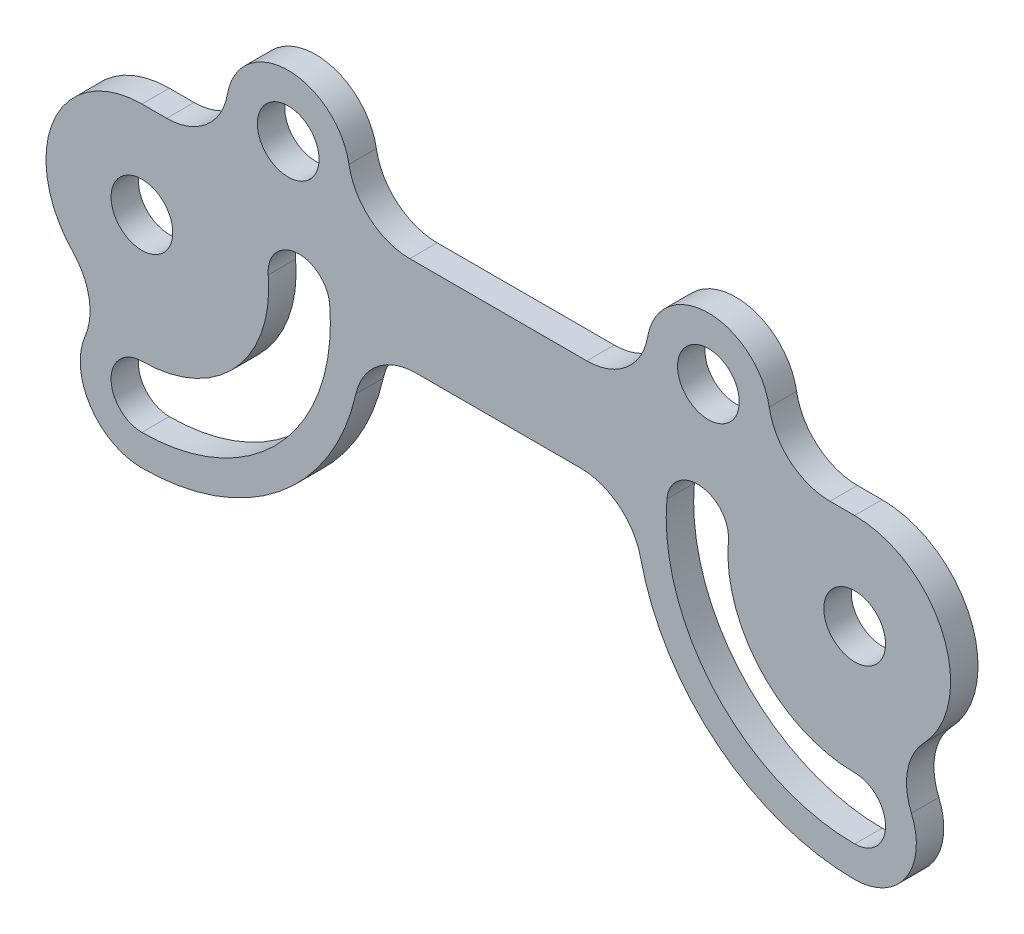
SolidWorks part; units mm, degrees
ref_plane "Front Plane" through (0, 0, 0) normal (0, 0, 1) x (1, 0, 0)
ref_plane "Top Plane" through (0, 0, 0) normal (0, 1, 0) x (1, 0, 0)
ref_plane "Right Plane" through (0, 0, 0) normal (1, 0, 0) x (0, 0, -1)
sketch "Sketch1" plane through (0, 0, 0) normal (0, 0, 1) x (1, 0, 0)
  line L14 (5.5562, 0) -> (35.7188, 0)
  line L15 (0, 5.5562) -> (41.275, 5.5562)
  line L16 (0, 5.5562) -> (0, -5.5562) construction
  line L17 (0, -5.5562) -> (41.275, -5.5562) construction
  line L18 (41.275, 5.5562) -> (41.275, -5.5562) construction
  line L19 (0, 5.5562) -> (41.275, 5.5562) construction
  line L21 (41.275, 0) -> (32.1816, 0.7956) construction
  line L22 (0, 0) -> (9.0934, 0.7956) construction
  line L23 (9.0934, 0.7956) -> (8.4708, 7.9121) construction
  line L24 (32.1816, 0.7956) -> (32.8042, 7.9121) construction
  circle A46 centre (0, 0) radius 5.5563 construction
  circle A47 centre (41.275, 0) radius 5.5563 construction
  arc A48 (0, 5.5562) -> (0, -5.5562) centre (0, 0) ccw
  arc A49 (41.275, -5.5562) -> (41.275, 5.5562) centre (41.275, 0) ccw
  circle A50 centre (0, 0) radius 1.7859
  circle A51 centre (41.275, 0) radius 1.7859
  arc A52 (0, -5.5562) -> (5.5562, 0) centre (0, 0) ccw
  arc A53 (35.7188, 0) -> (41.275, -5.5562) centre (41.275, 0) ccw
  circle A54 centre (41.275, 0) radius 9.1281 construction
  circle A55 centre (0, 0) radius 9.1281 construction
  circle A56 centre (41.275, -9.1281) radius 3.5719
  circle A57 centre (0, -9.1281) radius 3.5719
  circle A58 centre (0, -9.1281) radius 1.7859
  circle A59 centre (8.4708, 7.9121) radius 1.7859
  circle A60 centre (8.4708, 7.9121) radius 3.5719
  circle A61 centre (9.0934, 0.7956) radius 1.7859
  circle A62 centre (9.0934, 0.7956) radius 3.5719 construction
  circle A63 centre (32.1816, 0.7956) radius 1.7859
  circle A64 centre (32.1816, 0.7956) radius 3.5719 construction
  circle A65 centre (32.8042, 7.9121) radius 1.7859
  circle A66 centre (32.8042, 7.9121) radius 3.5719
  circle A67 centre (41.275, -9.1281) radius 1.7859
  arc A68 (7.3142, 0.6399) -> (0, -7.3422) centre (0, 0) cw
  arc A69 (0, -12.7) -> (12.6517, 1.1069) centre (0, 0) ccw
  arc A70 (0, -10.9141) -> (10.8725, 0.9512) centre (0, 0) ccw
  arc A71 (33.9608, 0.6399) -> (41.275, -7.3422) centre (41.275, 0) ccw
  arc A72 (30.4025, 0.9512) -> (41.275, -10.9141) centre (41.275, 0) ccw
  arc A73 (28.6233, 1.1069) -> (41.275, -12.7) centre (41.275, 0) ccw
  point P0 (0, 0)
  point P107 (-98.2589, 24.2017)
  point P108 (0, 0)
  dimension "D9" = 3.5719
  dimension "D10" = 41.275
  dimension "D11" = 11.1125
  dimension "D12" = 95
  dimension "D13" = 7.1437
  dimension "D14" = 95
extrude "Boss-Extrude1" add sketch "Sketch1" along normal blind 1.5875
fillet "Fillet1" radius 3.5719 8 edges at (41.275, -5.5562, 0.7937) (30.1194, 5.5562, 0.7937) (35.489, 5.5562, 0.7937) (28.575, 0, 0.7937) (12.7, 0, 0.7937) (5.786, 5.5562, 0.7937) (11.1556, 5.5562, 0.7937) (0, -5.5563, 0.7937)
